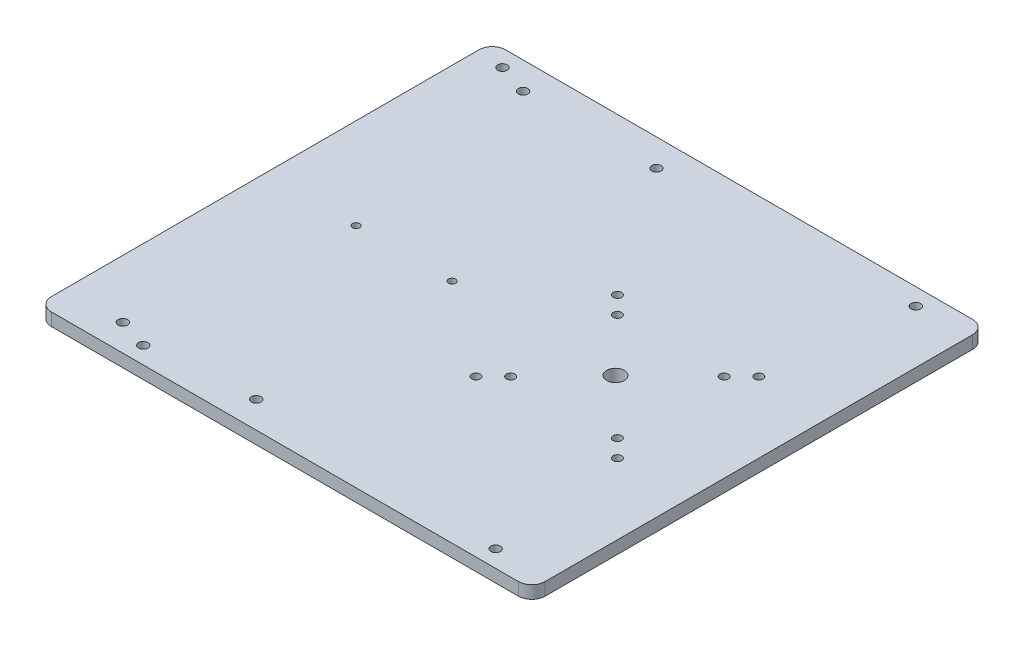
SolidWorks part; units mm, degrees
material "Acrylic (Medium-high impact)"
ref_plane "Front Plane" through (0, 0, 0) normal (0, 0, 1) x (1, 0, 0)
ref_plane "Top Plane" through (0, 0, 0) normal (0, 1, 0) x (1, 0, 0)
ref_plane "Right Plane" through (0, 0, 0) normal (1, 0, 0) x (0, 0, -1)
sketch "Sketch1" plane through (0, 0, 0) normal (0, 1, 0) x (1, 0, 0)
  line L1 (-87.5, 85.09) -> (87.5, 85.09)
  line L2 (-92.5, 80.09) -> (-92.5, -80.09)
  line L3 (-87.5, -85.09) -> (87.5, -85.09)
  line L4 (92.5, 80.09) -> (92.5, -80.09)
  line L5 (-92.5, 85.09) -> (92.5, -85.09) construction
  line L6 (-92.5, -85.09) -> (92.5, 85.09) construction
  arc A0 (-87.5, 85.09) -> (-92.5, 80.09) centre (-87.5, 80.09) ccw
  arc A1 (87.5, 85.09) -> (92.5, 80.09) centre (87.5, 80.09) cw
  arc A2 (87.5, -85.09) -> (92.5, -80.09) centre (87.5, -80.09) ccw
  arc A3 (-92.5, -80.09) -> (-87.5, -85.09) centre (-87.5, -80.09) ccw
  point P0 (0, 0)
  dimension "D3" = 5
  dimension "D1" = 170.18
  dimension "D2" = 185
extrude "Boss-Extrude1" add sketch "Sketch1" along normal blind 4.7625
sketch "Sketch4" plane through (0, 0, 0) normal (0, 1, 0) x (1, 0, 0)
  line L0 (-92.5, 80.09) -> (-92.5, -80.09) construction
  line L5 (-92.5, 85.09) -> (77.68, 85.09) construction
  line L6 (-92.5, 85.09) -> (-92.5, -85.09) construction
  line L7 (-92.5, -85.09) -> (77.68, -85.09) construction
  line L8 (77.68, 85.09) -> (77.68, -85.09) construction
  circle A0 centre (-59.48, -78.74) radius 1.778
  circle A1 centre (-82.32, 78.74) radius 1.778
  circle A2 centre (72.6, 78.74) radius 1.778
  circle A3 centre (72.6, -78.74) radius 1.778
  point P16 (-92.5, 0)
  point P19 (-92.5, 0)
  dimension "D1" = 3.556
  dimension "D2" = 5.08
  dimension "D3" = 170.18
  dimension "D4" = 6.35
  dimension "D5" = 6.35
  dimension "D6" = 10.18
  dimension "D7" = 33.02
extrude "jetson" cut sketch "Sketch4" along normal through all
sketch "Sketch2" [suppressed] plane through (0, 0, 0) normal (0, 1, 0) x (1, 0, 0)
  line L0 (-87.5, 56) -> (-87.5, -56) construction
  line L1 (-92.5, 80.09) -> (-92.5, -80.09) construction
  line L2 (82.68, 57.5) -> (82.68, -57.5) construction
  line L3 (92.5, -80.09) -> (92.5, 80.09) construction
  line L4 (77.68, 85.09) -> (77.68, -85.09) construction
  circle A0 centre (-87.5, 56) radius 1.778
  circle A1 centre (82.68, 57.5) radius 1.778
  circle A2 centre (82.68, -57.5) radius 1.778
  circle A3 centre (-87.5, -56) radius 1.778
  point P10 (-92.5, 0)
  point P11 (-87.5, 0)
  point P14 (92.5, 0)
  point P15 (82.68, 0)
  dimension "D1" = 3.556
  dimension "D2" = 5
  dimension "D3" = 112
  dimension "D4" = 115
  dimension "D5" = 5
extrude "bottom plate standoff" [suppressed] cut sketch "Sketch2" along normal through all
sketch "Sketch3" plane through (0, 0, 0) normal (0, 1, 0) x (1, 0, 0)
  line L0 (92.5, -80.09) -> (92.5, 80.09) construction
  line L1 (-58.4252, 0) -> (-22.4252, 0) construction
  circle A1 centre (-22.4252, 0) radius 1.35
  circle A2 centre (-58.4252, 0) radius 1.35
  circle A3 centre (-40.4252, 0) radius 15.5 construction
  point P5 (92.5, 0)
  dimension "D1" = 36
  dimension "D2" = 2.7
  dimension "D3" = 31
extrude "vmu931" cut sketch "Sketch3" along normal through all
sketch "Sketch6" plane through (0, 0, 0) normal (0, 1, 0) x (1, 0, 0)
  line L0 (92.5, -80.09) -> (92.5, 80.09) construction
  line L1 (19.5093, 20) -> (59.5093, 20) construction
  line L2 (19.5093, 20) -> (19.5093, -20) construction
  line L3 (19.5093, -20) -> (59.5093, -20) construction
  line L4 (59.5093, 20) -> (59.5093, -20) construction
  line L5 (19.5093, 20) -> (59.5093, -20) construction
  line L6 (19.5093, -20) -> (59.5093, 20) construction
  line L8 (14.5093, 25) -> (64.5093, 25) construction
  line L9 (14.5093, 25) -> (14.5093, -25) construction
  line L10 (14.5093, -25) -> (64.5093, -25) construction
  line L11 (64.5093, 25) -> (64.5093, -25) construction
  line L12 (14.5093, 25) -> (64.5093, -25) construction
  line L13 (14.5093, -25) -> (64.5093, 25) construction
  circle A0 centre (59.5093, 20) radius 1.59
  circle A1 centre (59.5093, -20) radius 1.59
  circle A2 centre (19.5093, -20) radius 1.59
  circle A3 centre (19.5093, 20) radius 1.59
  point P0 (39.5093, 0)
  point P8 (92.5, 0)
  point P12 (39.5093, 0)
  dimension "D2" = 3.18
  dimension "D1" = 40
  dimension "D3" = 50
extrude "lidar urg/ust" cut sketch "Sketch6" along normal through all
sketch "Sketch7" plane through (0, 0, 0) normal (0, 1, 0) x (1, 0, 0)
  line L0 (92.5, -80.09) -> (92.5, 80.09) construction
  line L1 (13.0093, 26.5) -> (66.0093, 26.5) construction
  line L2 (13.0093, 26.5) -> (13.0093, -26.5) construction
  line L3 (13.0093, -26.5) -> (66.0093, -26.5) construction
  line L4 (66.0093, 26.5) -> (66.0093, -26.5) construction
  line L5 (13.0093, 26.5) -> (66.0093, -26.5) construction
  line L6 (13.0093, -26.5) -> (66.0093, 26.5) construction
  line L7 (19.5093, 20) -> (59.5093, -20) construction
  line L8 (8.5093, 31) -> (70.5093, 31) construction
  line L9 (8.5093, 31) -> (8.5093, -31) construction
  line L10 (8.5093, -31) -> (70.5093, -31) construction
  line L11 (70.5093, 31) -> (70.5093, -31) construction
  line L12 (8.5093, 31) -> (70.5093, -31) construction
  line L13 (8.5093, -31) -> (70.5093, 31) construction
  circle A0 centre (13.0093, 26.5) radius 1.59
  circle A1 centre (13.0093, -26.5) radius 1.59
  circle A2 centre (66.0093, -26.5) radius 1.59
  circle A3 centre (66.0093, 26.5) radius 1.59
  point P0 (39.5093, 0)
  point P8 (92.5, 0)
  point P12 (39.5093, 0)
  dimension "D2" = 3.18
  dimension "D1" = 53
  dimension "D3" = 62
extrude "lidar utm" cut sketch "Sketch7" along normal through all
sketch "Sketch9" plane through (0, 0, 0) normal (0, 1, 0) x (1, 0, 0)
  line L0 (92.5, -80.09) -> (92.5, 80.09) construction
  line L1 (-58.4252, 0) -> (-22.4252, 0) construction
  circle A0 centre (38.7933, 0) radius 51.65 construction
  circle A1 centre (38.7933, 0) radius 3.3
  point P7 (92.5, 0)
  dimension "D1" = 6.6
  dimension "D2" = 103.3
extrude "lidar velodyne" cut sketch "Sketch9" along normal through all
sketch "Sketch5" plane through (0, 0, 0) normal (0, 1, 0) x (1, 0, 0)
  line L0 (92.5, -80.09) -> (92.5, 80.09) construction
  line L1 (-87.5, -85.09) -> (87.5, -85.09) construction
  line L3 (87.5, 85.09) -> (-87.5, 85.09) construction
  line L4 (92.5, -80.09) -> (92.5, 80.09)
  line L5 (3.0238, -85.09) -> (87.5, -85.09)
  line L7 (87.5, 85.09) -> (3.0238, 85.09)
  line L8 (64.3576, 44.3796) -> (86.9627, 44.3796)
  line L9 (88.4627, 42.8796) -> (88.4627, 40.6591)
  line L10 (86.9627, 39.1591) -> (83.0648, 39.1591)
  line L11 (81.5648, 37.6591) -> (81.5648, -37.6591)
  line L12 (-100, 0) -> (92.5, 0) construction
  line L13 (86.9627, -39.1591) -> (83.0648, -39.1591)
  line L14 (88.4627, -42.8796) -> (88.4627, -40.6591)
  line L15 (64.3576, -44.3796) -> (86.9627, -44.3796)
  arc A0 (92.5, 80.09) -> (87.5, 85.09) centre (87.5, 80.09) ccw construction
  arc A1 (87.5, -85.09) -> (92.5, -80.09) centre (87.5, -80.09) ccw construction
  arc A4 (92.5, 80.09) -> (87.5, 85.09) centre (87.5, 80.09) ccw
  arc A5 (87.5, -85.09) -> (92.5, -80.09) centre (87.5, -80.09) ccw
  arc A8 (83.0648, 39.1591) -> (81.5648, 37.6591) centre (83.0648, 37.6591) ccw
  arc A9 (86.9627, 44.3796) -> (88.4627, 42.8796) centre (86.9627, 42.8796) cw
  arc A10 (88.4627, 40.6591) -> (86.9627, 39.1591) centre (86.9627, 40.6591) cw
  arc A11 (83.0648, -39.1591) -> (81.5648, -37.6591) centre (83.0648, -37.6591) cw
  arc A12 (88.4627, -40.6591) -> (86.9627, -39.1591) centre (86.9627, -40.6591) ccw
  arc A13 (86.9627, -44.3796) -> (88.4627, -42.8796) centre (86.9627, -42.8796) ccw
  spline S0 degree 3 poles (3.0238, 85.09) (34.6269, 85.09) (33.552, 44.3796) (64.3576, 44.3796) knots 0 0 0 0 1 1 1 1
  spline S1 degree 3 poles (3.0238, -85.09) (34.6269, -85.09) (33.552, -44.3796) (64.3576, -44.3796) knots 0 0 0 0 1 1 1 1
  point P19 (81.5648, 0)
  dimension "D1" = 1.5
extrude "Cut-Extrude4" [suppressed] cut sketch "Sketch5" along normal through all
sketch "Sketch10" plane through (0, 4.7625, 0) normal (0, 1, 0) x (1, 0, 0)
  line L0 (-92.5, -85.09) -> (77.68, -85.09) construction
  line L1 (-70.7598, 74.91) -> (-20.7598, 74.91) construction
  line L2 (-70.7598, 74.91) -> (-70.7598, -75.09) construction
  line L3 (-70.7598, -75.09) -> (-20.7598, -75.09) construction
  line L4 (-20.7598, 74.91) -> (-20.7598, -75.09) construction
  circle A1 centre (-70.7598, 74.91) radius 1.78
  circle A2 centre (-20.7598, 74.91) radius 1.78
  circle A3 centre (-70.7598, -75.09) radius 1.78
  circle A4 centre (-20.7598, -75.09) radius 1.78
  dimension "D1" = 150
  dimension "D2" = 50
  dimension "D3" = 10
extrude "Cut-Extrude5" cut sketch "Sketch10" against normal through all
